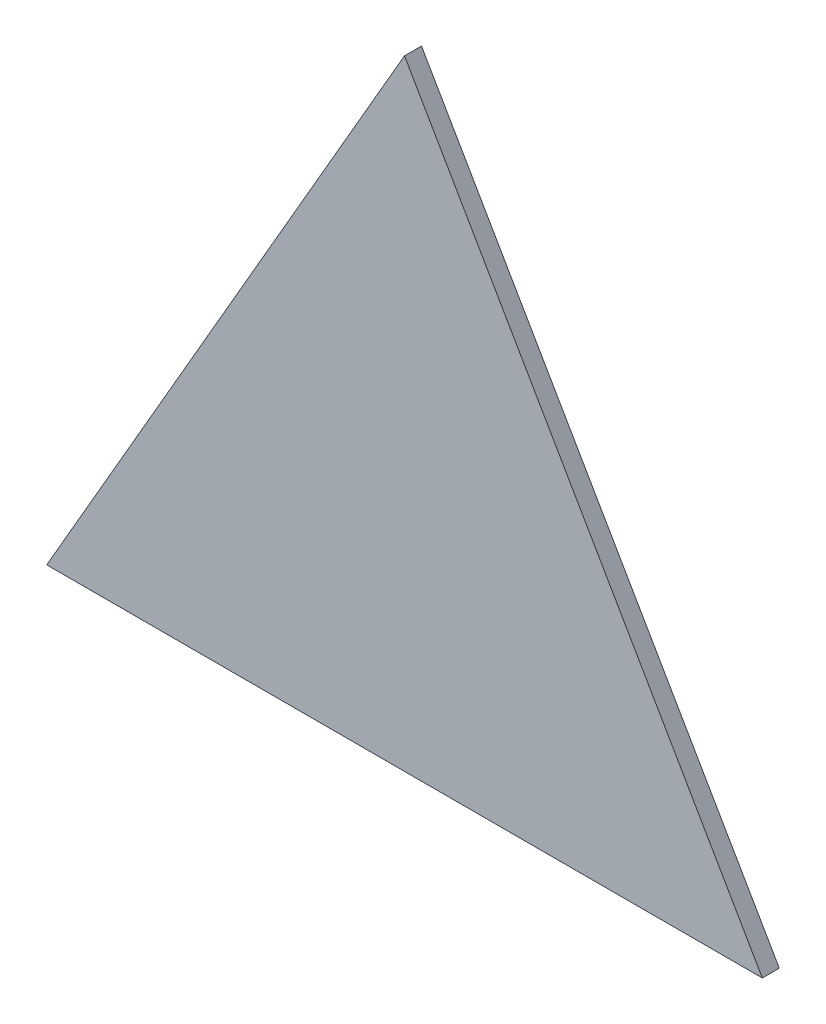
SolidWorks part; units mm, degrees
ref_plane "Front Plane" through (0, 0, 0) normal (0, 0, 1) x (1, 0, 0)
ref_plane "Top Plane" through (0, 0, 0) normal (0, 1, 0) x (1, 0, 0)
ref_plane "Right Plane" through (0, 0, 0) normal (1, 0, 0) x (0, 0, -1)
sketch "Sketch1" plane through (0, 0, 0) normal (0, 0, 1) x (1, 0, 0)
  line L0 (0, 36.5) -> (-42.1466, -36.5)
  line L1 (-42.1466, -36.5) -> (42.1466, -36.5)
  line L2 (42.1466, -36.5) -> (0, 36.5)
  point P2 (0, -36.5)
  point P4 (-21.0733, 0)
  point P6 (0, 36.5)
  dimension "D1" = 73
extrude "Boss-Extrude1" add sketch "Sketch1" along normal blind 2
